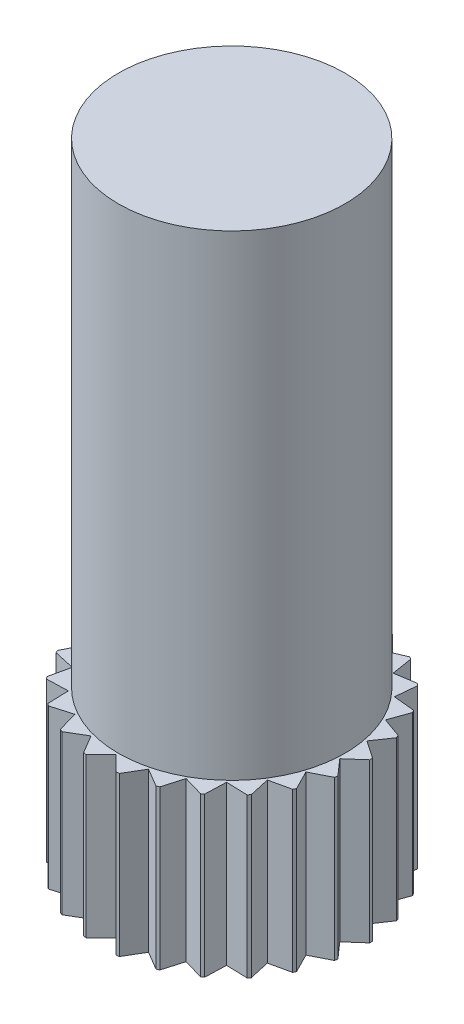
SolidWorks part; units mm, degrees
material "黄铜"
ref_plane "前视基准面" through (0, 0, 0) normal (0, 0, 1) x (1, 0, 0)
ref_plane "上视基准面" through (0, 0, 0) normal (0, 1, 0) x (1, 0, 0)
ref_plane "右视基准面" through (0, 0, 0) normal (1, 0, 0) x (0, 0, -1)
sketch "草图1" plane through (0, 0, 0) normal (0, 1, 0) x (1, 0, 0)
  circle A0 centre (0, 0) radius 2.9
  dimension "D1" = 5.8
extrude "凸台-拉伸1" add sketch "草图1" along normal blind 3.5
sketch "草图2" plane through (0, 3.5, 0) normal (0, 1, 0) x (1, 0, 0)
  circle A0 centre (0, 0) radius 2.5
  dimension "D1" = 5
extrude "凸台-拉伸2" add sketch "草图2" along normal blind 10.5
sketch "草图3" plane through (0, 0, 0) normal (0, -1, 0) x (1, 0, 0)
  line L0 (0, 2.55) -> (0.3665, 2.9165)
  line L1 (0, 2.55) -> (-0.3665, 2.9165)
  line L2 (0.9313, 2.55) -> (-0.9313, 2.55) construction
  line L3 (0, 2.55) -> (-0.3665, 2.9165)
  line L4 (-0.3665, 2.9165) -> (0.3665, 2.9165)
  line L5 (0.3665, 2.9165) -> (0, 2.55)
  line L6 (0.6342, 2.4699) -> (1.0803, 2.7337)
  line L7 (0.6342, 2.4699) -> (0.3703, 2.916)
  line L8 (0.3703, 2.916) -> (1.0803, 2.7337)
  line L9 (1.2285, 2.2346) -> (1.7262, 2.3792)
  line L10 (1.2285, 2.2346) -> (1.0839, 2.7323)
  line L11 (1.0839, 2.7323) -> (1.7262, 2.3792)
  line L12 (1.7456, 1.8589) -> (2.2636, 1.8752)
  line L13 (1.7456, 1.8589) -> (1.7293, 2.3769)
  line L14 (1.7293, 2.3769) -> (2.2636, 1.8752)
  line L15 (2.153, 1.3664) -> (2.6589, 1.2533)
  line L16 (2.153, 1.3664) -> (2.2661, 1.8722)
  line L17 (2.2661, 1.8722) -> (2.6589, 1.2533)
  line L18 (2.4252, 0.788) -> (2.887, 0.5527)
  line L19 (2.4252, 0.788) -> (2.6605, 1.2498)
  line L20 (2.6605, 1.2498) -> (2.887, 0.5527)
  line L21 (2.545, 0.1601) -> (2.9338, -0.1826)
  line L22 (2.545, 0.1601) -> (2.8877, 0.5489)
  line L23 (2.8877, 0.5489) -> (2.9338, -0.1826)
  line L24 (2.5048, -0.4778) -> (2.7962, -0.9065)
  line L25 (2.5048, -0.4778) -> (2.9335, -0.1865)
  line L26 (2.9335, -0.1865) -> (2.7962, -0.9065)
  line L27 (2.3073, -1.0857) -> (2.4829, -1.5734)
  line L28 (2.3073, -1.0857) -> (2.795, -0.9102)
  line L29 (2.795, -0.9102) -> (2.4829, -1.5734)
  line L30 (1.9648, -1.6254) -> (2.0136, -2.1414)
  line L31 (1.9648, -1.6254) -> (2.4808, -1.5767)
  line L32 (2.4808, -1.5767) -> (2.0136, -2.1414)
  line L33 (1.4989, -2.063) -> (1.4178, -2.5749)
  line L34 (1.4989, -2.063) -> (2.0108, -2.1441)
  line L35 (2.0108, -2.1441) -> (1.4178, -2.5749)
  line L36 (0.9387, -2.3709) -> (0.7329, -2.8466)
  line L37 (0.9387, -2.3709) -> (1.4144, -2.5768)
  line L38 (1.4144, -2.5768) -> (0.7329, -2.8466)
  line L39 (0.3196, -2.5299) -> (0.0019, -2.9394)
  line L40 (0.3196, -2.5299) -> (0.7291, -2.8476)
  line L41 (0.7291, -2.8476) -> (0.0019, -2.9394)
  line L42 (-0.3196, -2.5299) -> (-0.7291, -2.8476)
  line L43 (-0.3196, -2.5299) -> (-0.0019, -2.9394)
  line L44 (-0.0019, -2.9394) -> (-0.7291, -2.8476)
  line L45 (-0.9387, -2.3709) -> (-1.4144, -2.5768)
  line L46 (-0.9387, -2.3709) -> (-0.7329, -2.8466)
  line L47 (-0.7329, -2.8466) -> (-1.4144, -2.5768)
  line L48 (-1.4989, -2.063) -> (-2.0108, -2.1441)
  line L49 (-1.4989, -2.063) -> (-1.4178, -2.5749)
  line L50 (-1.4178, -2.5749) -> (-2.0108, -2.1441)
  line L51 (-1.9648, -1.6254) -> (-2.4808, -1.5767)
  line L52 (-1.9648, -1.6254) -> (-2.0136, -2.1414)
  line L53 (-2.0136, -2.1414) -> (-2.4808, -1.5767)
  line L54 (-2.3073, -1.0857) -> (-2.795, -0.9102)
  line L55 (-2.3073, -1.0857) -> (-2.4829, -1.5734)
  line L56 (-2.4829, -1.5734) -> (-2.795, -0.9102)
  line L57 (-2.5048, -0.4778) -> (-2.9335, -0.1865)
  line L58 (-2.5048, -0.4778) -> (-2.7962, -0.9065)
  line L59 (-2.7962, -0.9065) -> (-2.9335, -0.1865)
  line L60 (-2.545, 0.1601) -> (-2.8877, 0.5489)
  line L61 (-2.545, 0.1601) -> (-2.9338, -0.1826)
  line L62 (-2.9338, -0.1826) -> (-2.8877, 0.5489)
  line L63 (-2.4252, 0.788) -> (-2.6605, 1.2498)
  line L64 (-2.4252, 0.788) -> (-2.887, 0.5527)
  line L65 (-2.887, 0.5527) -> (-2.6605, 1.2498)
  line L66 (-2.153, 1.3664) -> (-2.2661, 1.8722)
  line L67 (-2.153, 1.3664) -> (-2.6589, 1.2533)
  line L68 (-2.6589, 1.2533) -> (-2.2661, 1.8722)
  line L69 (-1.7456, 1.8589) -> (-1.7293, 2.3769)
  line L70 (-1.7456, 1.8589) -> (-2.2636, 1.8752)
  line L71 (-2.2636, 1.8752) -> (-1.7293, 2.3769)
  line L72 (-1.2285, 2.2346) -> (-1.0839, 2.7323)
  line L73 (-1.2285, 2.2346) -> (-1.7262, 2.3792)
  line L74 (-1.7262, 2.3792) -> (-1.0839, 2.7323)
  line L75 (-0.6342, 2.4699) -> (-0.3703, 2.916)
  line L76 (-0.6342, 2.4699) -> (-1.0803, 2.7337)
  line L77 (-1.0803, 2.7337) -> (-0.3703, 2.916)
  circle A0 centre (0, 0) radius 2.55 construction
  point P9 (0, 2.55)
  point P84 (0, 0)
  circle M79 centre (0, 0) radius 2.9
  dimension "D1" = 5.1
  dimension "D2" = 25
  dimension "D4" = 0.733
  dimension "D5" = 90
extrude "切除-拉伸1" cut sketch "草图3" against normal up to surface (3.5 mm away) contours L7 L6 M79 | L1 L0 M79 | L4 L1 L0 M79 | L8 L7 L6 M79 | L64 L63 M79 | L65 L64 L63 M79 | L62 L61 L60 M79 | L61 L60 M79 | L58 L57 M79 | L59 L58 L57 M79 | L55 L54 M79 | L56 L55 L54 M79 | L52 L51 M79 | L53 L52 L51 M79 | L49 L48 M79 | L50 L49 L48 M79 | L46 L45 M79 | L47 L46 L45 M79 | L43 L42 M79 | L44 L43 L42 M79 | L40 L39 M79 | L41 L40 L39 M79 | L37 L36 M79 | L38 L37 L36 M79 | L34 L33 M79 | L35 L34 L33 M79 | L32 L31 L30 M79 | L31 L30 M79 | L29 L28 L27 M79 | L28 L27 M79 | L26 L25 L24 M79 | L25 L24 M79 | L23 L22 L21 M79 | L22 L21 M79 | L20 L19 L18 M79 | L19 L18 M79 | L17 L16 L15 M79 | L16 L15 M79 | L14 L13 L12 M79 | L13 L12 M79 | L10 L9 M79 | L11 L10 L9 M79 | L77 L75 L76 | L74 L72 L73 | L71 L69 L70 | L66 L68 L67
hole_wizard "M3 螺旋的螺纹孔钻头1" positions "草图6" profile "草图7" hole size "M3x0.5" standard "DIN"
sketch "草图6" plane through (0, 0, 0) normal (0, -1, 0) x (-1, 0, 0)
  point P0 (0, 0)
sketch "草图7" plane through (0, 0, 0) normal (1, 0, 0) x (0, 0, -1)
  line L0 (0, 0) -> (0, 9.25)
  line L1 (0, 9.25) -> (1.25, 8)
  line L2 (1.25, 8) -> (1.25, 0.35)
  line L3 (1.25, 0.35) -> (1.6, 0)
  line L5 (1.6, 0) -> (0, 0)
  line L6 (-1.25, 0.35) -> (-1.6, 0) construction
  line L10 (0, 9.25) -> (-1.25, 8) construction
  line L11 (0, -6.35) -> (0, 107.95) construction
  dimension "孔直径" = 2.5
  dimension "孔深度" = 8
  dimension "近端锥形沉头孔直径" = 3.2
  dimension "近端锥形沉头孔角度" = 90
  dimension "导头角度" = 90
cosmetic thread "装饰螺纹线2" parameters "D2"=3
